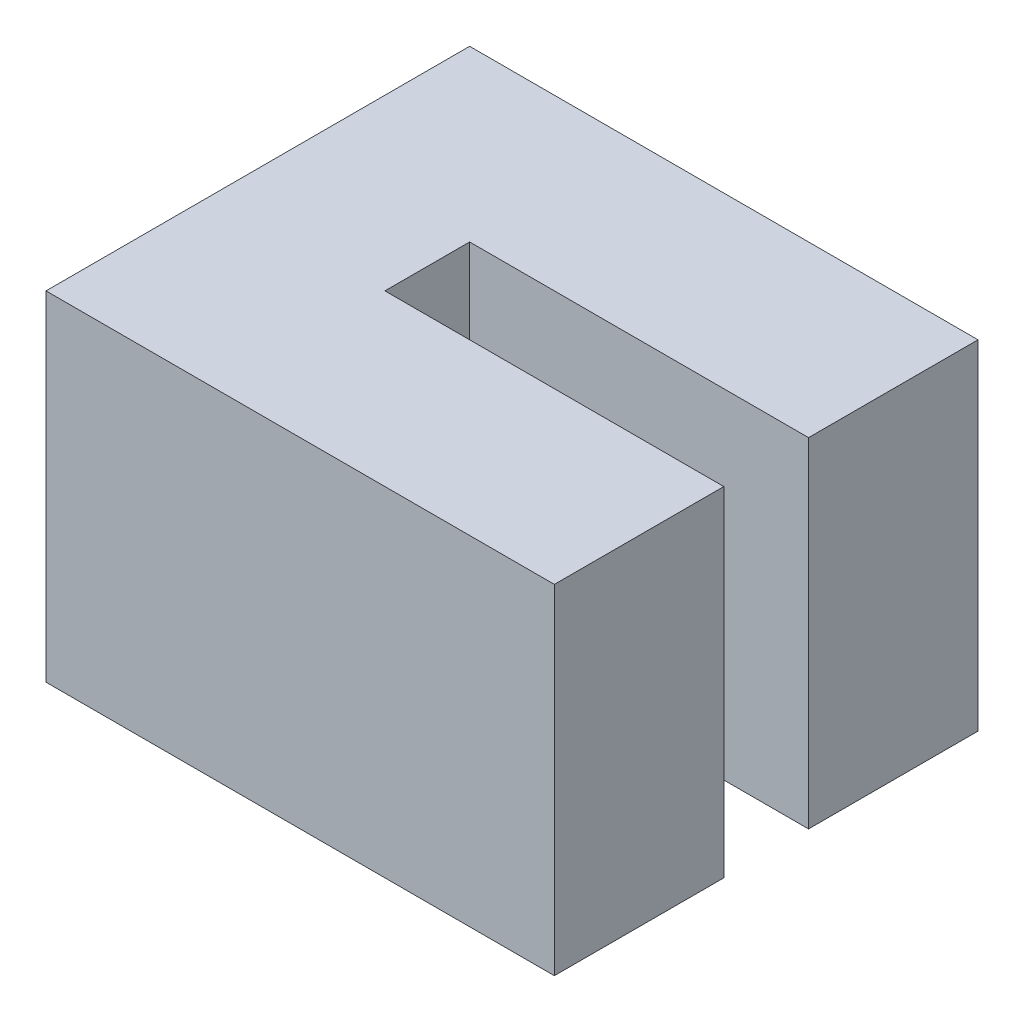
SolidWorks part; units mm, degrees
ref_plane "Přední rovina" through (0, 0, 0) normal (0, 0, 1) x (1, 0, 0)
ref_plane "Horní rovina" through (0, 0, 0) normal (0, 1, 0) x (1, 0, 0)
ref_plane "Pravá rovina" through (0, 0, 0) normal (1, 0, 0) x (0, 0, -1)
sketch "Sketch1" plane through (0, 0, 0) normal (0, 1, 0) x (1, 0, 0)
  line L0 (0, 0) -> (0, -25)
  line L1 (0, -25) -> (30, -25)
  line L2 (30, -25) -> (30, -15)
  line L3 (30, -15) -> (10, -15)
  line L4 (10, -15) -> (10, -10)
  line L5 (10, -10) -> (30, -10)
  line L6 (30, -10) -> (30, 0)
  line L7 (30, 0) -> (0, 0)
  dimension "D1" = 10
  dimension "D2" = 10
  dimension "D3" = 5
  dimension "D4" = 10
  dimension "D5" = 20
extrude "Boss-Extrude1" add sketch "Sketch1" along normal blind 20
equation "\"H\"= 5"
equation "\"D3@Sketch1\"=\"H\""
equation "\"L\"= 20"
equation "\"D5@Sketch1\"=\"L\""
